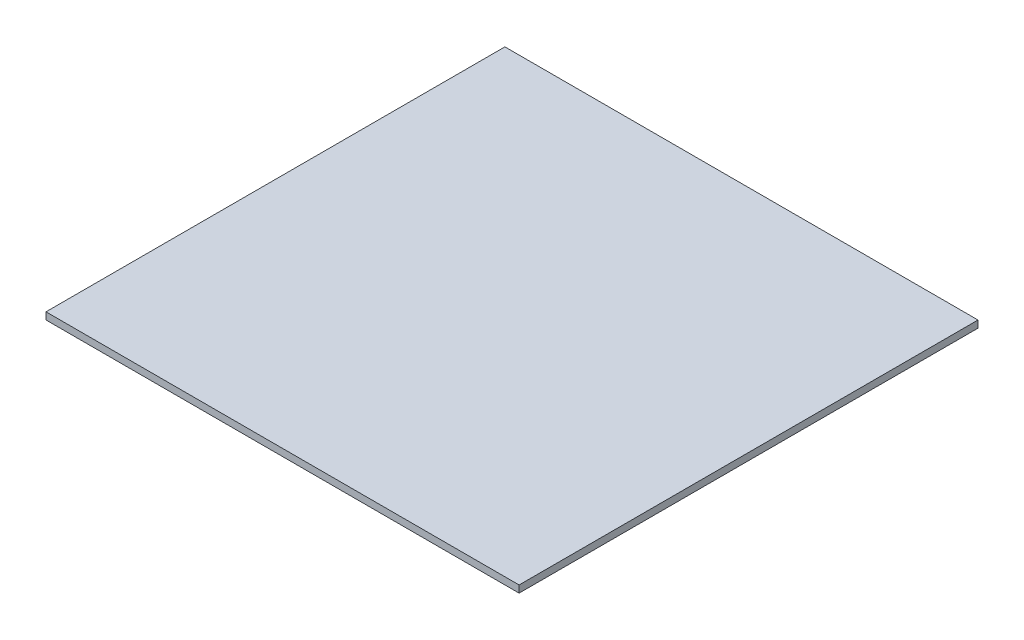
SolidWorks part; units mm, degrees
ref_plane "Front Plane" through (0, 0, 0) normal (0, 0, 1) x (1, 0, 0)
ref_plane "Top Plane" through (0, 0, 0) normal (0, 1, 0) x (1, 0, 0)
ref_plane "Right Plane" through (0, 0, 0) normal (1, 0, 0) x (0, 0, -1)
sketch "Sketch1" plane through (0, 0, 0) normal (0, 1, 0) x (1, 0, 0)
  line L1 (0, 0) -> (200, 0)
  line L2 (0, 0) -> (0, -194)
  line L3 (0, -194) -> (200, -194)
  line L4 (200, 0) -> (200, -194)
  dimension "D1" = 194
  dimension "D2" = 200
extrude "Boss-Extrude1" add sketch "Sketch1" along normal blind 3
